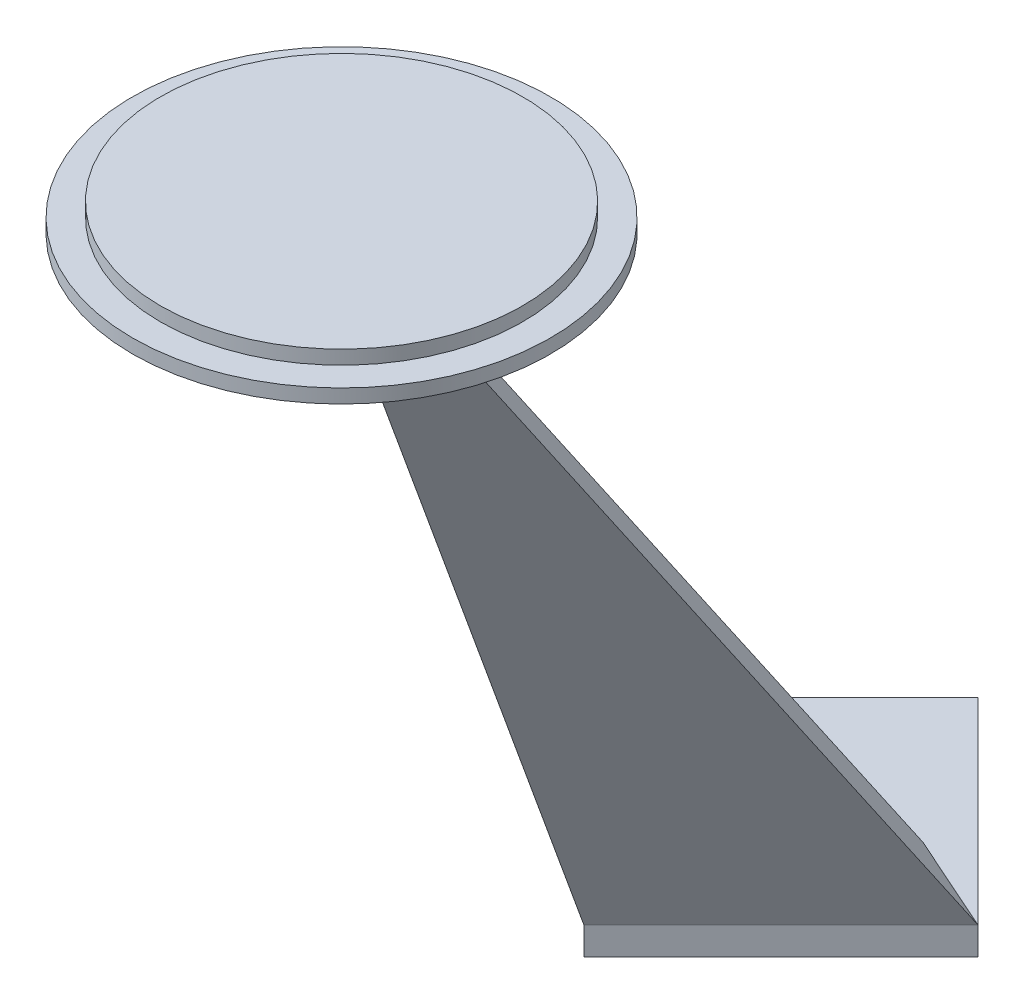
SolidWorks part; units mm, degrees
ref_plane "Front Plane" through (0, 0, 0) normal (0, 0, 1) x (1, 0, 0)
ref_plane "Top Plane" through (0, 0, 0) normal (0, 1, 0) x (1, 0, 0)
ref_plane "Right Plane" through (0, 0, 0) normal (1, 0, 0) x (0, 0, -1)
sketch "Sketch1" plane through (0, 0, 0) normal (0, 1, 0) x (1, 0, 0)
  line L1 (0, 14.1421) -> (-14.1421, 0)
  line L2 (-14.1421, 0) -> (0, -14.1421)
  line L3 (0, -14.1421) -> (14.1421, 0)
  line L4 (14.1421, 0) -> (0, 14.1421)
  circle A0 centre (0, 0) radius 1.5
  dimension "D1" = 20
extrude "Boss-Extrude2" add sketch "Sketch1" along normal blind 2
sketch "Sketch3" plane through (0, 2, 0) normal (0, 1, 0) x (1, 0, 0)
  line L5 (0, -14.1421) -> (14.1421, 0)
  line L8 (-14.1421, 0) -> (0, -14.1421)
  line L9 (0, -12) -> (12, 0)
  line L12 (-12, 0) -> (0, -12)
  line L14 (-14.1421, 0) -> (-12, 0)
  line L15 (0, 12) -> (-12, 0) [skipped]
  line L16 (12, 0) -> (0, 12) [skipped]
  line L17 (12, 0) -> (14.1421, 0)
  line L18 (-13.0711, 1.0711) -> (-14.1421, 0) [skipped]
  line L19 (14.1421, 0) -> (13.0711, 1.0711) [skipped]
sketch "Sketch4" plane through (0, 0, 0) normal (1, 0, 0) x (0, 0, -1)
  line L0 (-356.1623, 941.6926) -> (16744.8449, -46042.9384) construction
extrude "Boss-Extrude3" add sketch "Sketch3" along direction (0, -0.9397, -0.342) on the side of the normal blind 55
sketch "Sketch5" plane through (6.2904, -2.2895, 6.2904) normal (0.6848, -0.2492, 0.6848) x (0.6435, -0.2342, -0.7287)
  line L1 (8.6319, 6.7163) -> (-17.1813, 55.2825)
  line L3 (-17.1813, 55.2825) -> (-34.6469, 50.9293)
  line L4 (-36.5876, 50.4456) -> (-17.1813, 55.2825) construction
  line L5 (8.6319, 6.7163) -> (-34.6469, 50.9293)
  dimension "D1" = 18
extrude "Cut-Extrude1" cut sketch "Sketch5" against normal blind 2
sketch "Sketch6" plane through (-6.2904, -2.2895, 6.2904) normal (-0.6848, -0.2492, 0.6848) x (0.6435, 0.2342, 0.7287)
  line L0 (17.1813, 55.2825) -> (34.6469, 50.9293)
  line L1 (17.1813, 55.2825) -> (36.5876, 50.4456) construction
  line L2 (17.1813, 55.2825) -> (-8.6319, 6.7163)
  line L3 (-8.6319, 6.7163) -> (34.6469, 50.9293)
  dimension "D1" = 18
extrude "Cut-Extrude2" cut sketch "Sketch6" against normal blind 2
sketch "Sketch8" plane through (0, 53.6831, 0) normal (0, 1, 0) x (1, 0, 0)
  circle A0 centre (0, -31.539) radius 15
extrude "Boss-Extrude6" add sketch "Sketch8" along normal blind 2 contours A0
sketch "Sketch12" plane through (0, 55.6831, 0) normal (0, 1, 0) x (1, 0, 0)
  circle A0 centre (0, -31.539) radius 13
  circle A1 centre (0, -31.539) radius 15
extrude "Cut-Extrude3" cut sketch "Sketch12" against normal blind 1
